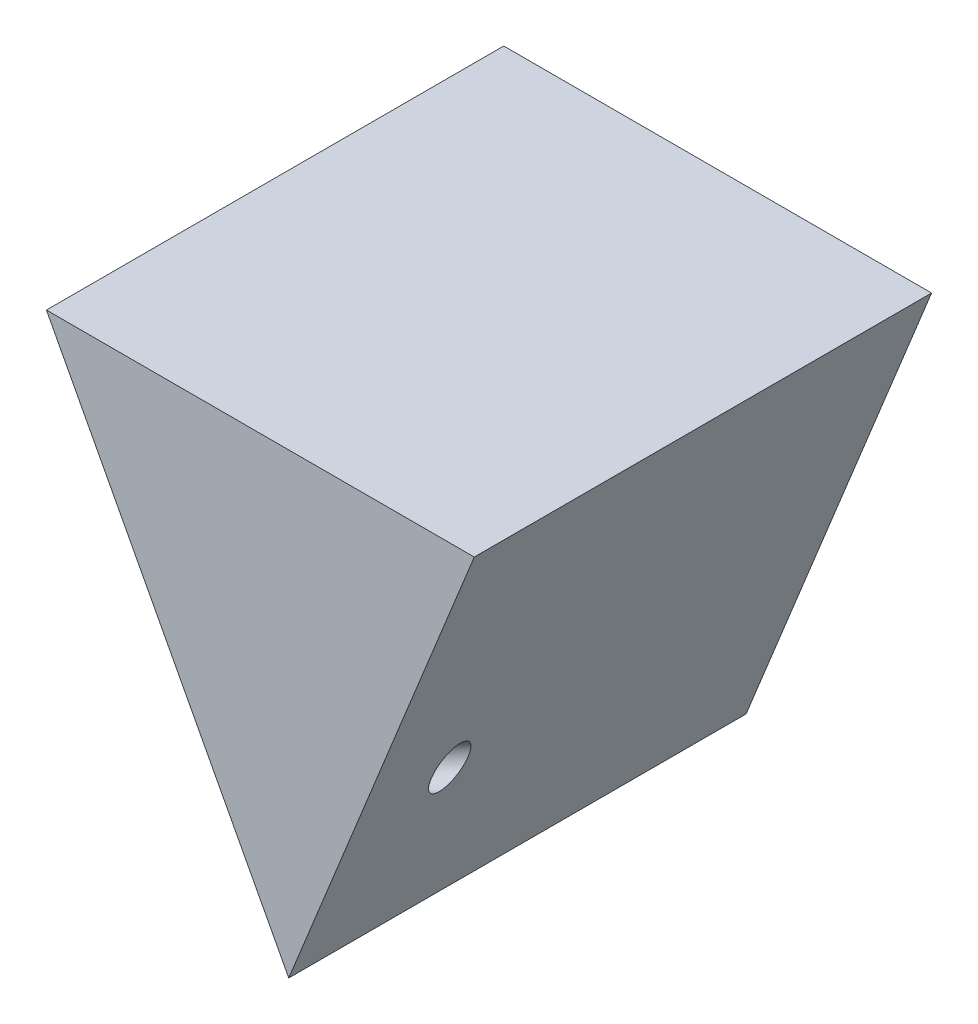
SolidWorks part; units mm, degrees
material "ABS"
ref_plane "Front Plane" through (0, 0, 0) normal (0, 0, 1) x (1, 0, 0)
ref_plane "Top Plane" through (0, 0, 0) normal (0, 1, 0) x (1, 0, 0)
ref_plane "Right Plane" through (0, 0, 0) normal (1, 0, 0) x (0, 0, -1)
sketch "Sketch1" plane through (0, 0, 0) normal (0, 0, 1) x (1, 0, 0)
  line L0 (-36.2386, 19.2413) -> (-9.7428, -30.7587)
  line L1 (-9.7428, -30.7587) -> (10.5399, 19.2413)
  line L2 (10.5399, 19.2413) -> (-36.2386, 19.2413)
  dimension "D1" = 50
  dimension "D2" = 50
  dimension "D3" = 50
extrude "Boss-Extrude1" add sketch "Sketch1" along normal blind 50
sketch "Sketch2" plane through (-20.3326, -10.7746, 0) normal (-0.8836, -0.4682, 0) x (0, 0, 1)
  line L0 (50, 33.97) -> (50, -22.6165) construction
  line L1 (50, -22.6165) -> (0, -22.6165) construction
  circle A0 centre (40, -9.6165) radius 2
  dimension "D1" = 4
  dimension "D2" = 10
  dimension "D3" = 13
extrude "Cut-Extrude1" cut sketch "Sketch2" against normal blind 50
